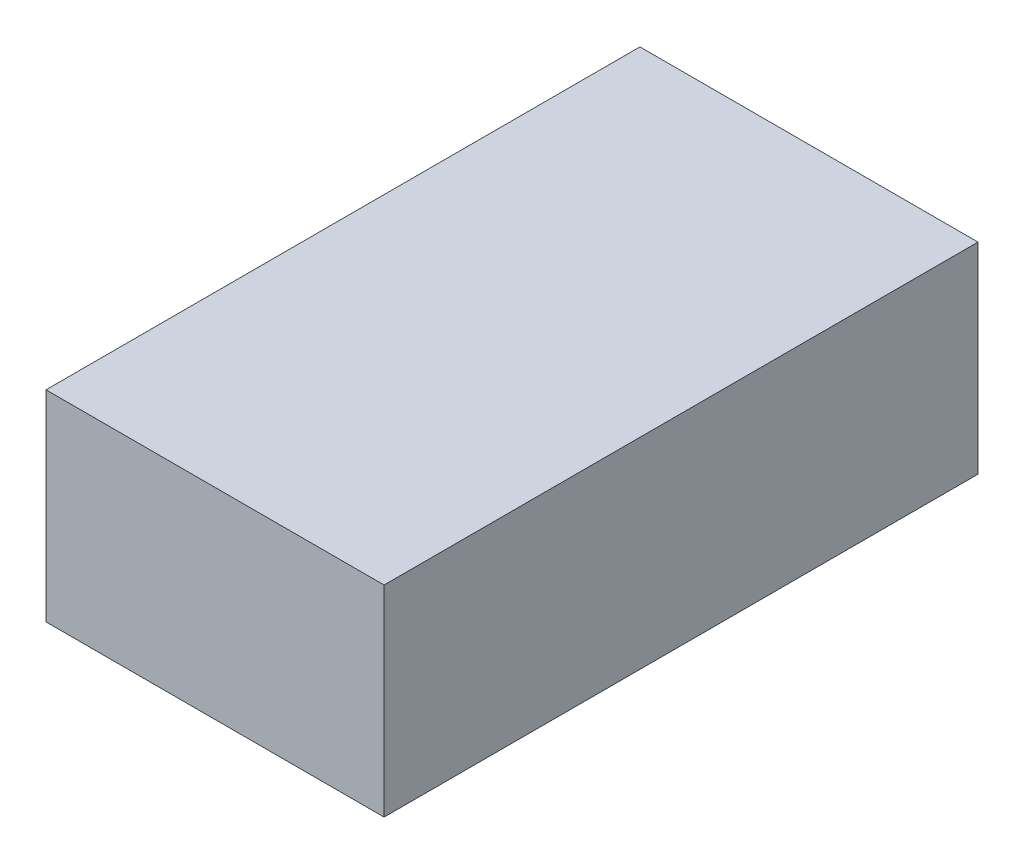
SolidWorks part; units mm, degrees
ref_plane "Front Plane" through (0, 0, 0) normal (0, 0, 1) x (1, 0, 0)
ref_plane "Top Plane" through (0, 0, 0) normal (0, 1, 0) x (1, 0, 0)
ref_plane "Right Plane" through (0, 0, 0) normal (1, 0, 0) x (0, 0, -1)
sketch "Sketch1" plane through (0, 0, 0) normal (0, 0, 1) x (1, 0, 0)
  line L1 (-18.5, -11) -> (18.5, -11)
  line L2 (-18.5, -11) -> (-18.5, 11)
  line L3 (-18.5, 11) -> (18.5, 11)
  line L4 (18.5, -11) -> (18.5, 11)
  line L5 (-18.5, -11) -> (18.5, 11) construction
  line L6 (-18.5, 11) -> (18.5, -11) construction
  point P0 (0, 0)
  dimension "D1" = 37
  dimension "D2" = 22
extrude "Boss-Extrude1" add sketch "Sketch1" along normal mid plane 65
